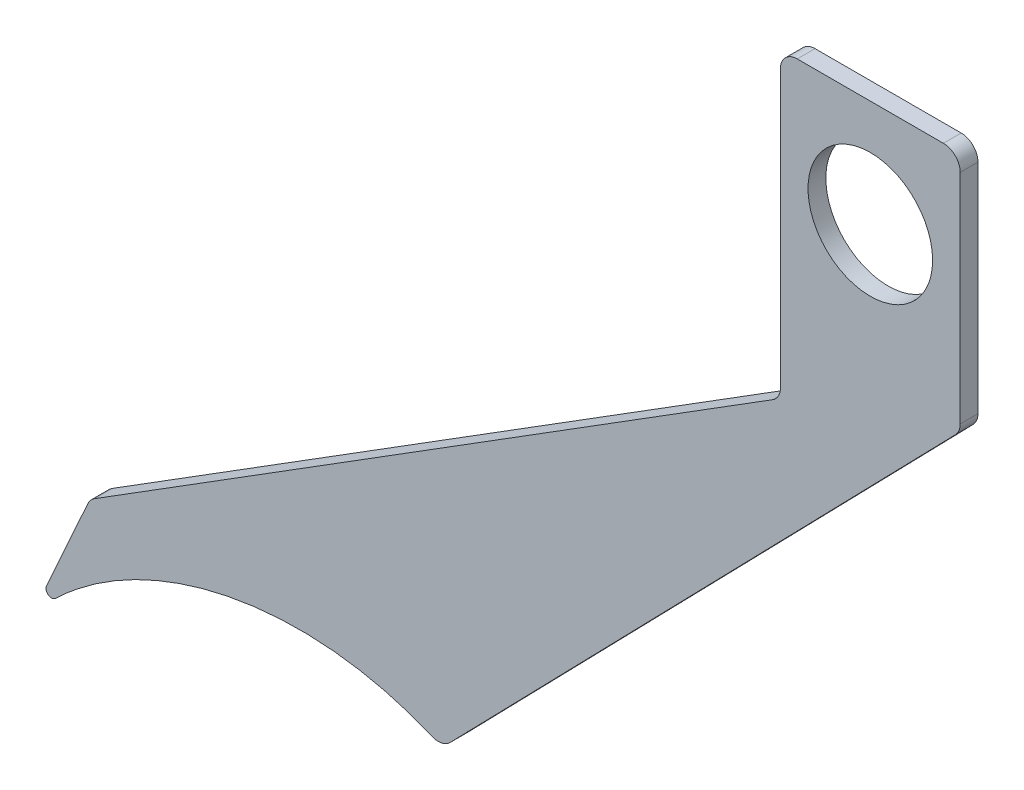
SolidWorks part; units mm, degrees
ref_plane "Front Plane" through (0, 0, 0) normal (0, 0, 1) x (1, 0, 0)
ref_plane "Top Plane" through (0, 0, 0) normal (0, 1, 0) x (1, 0, 0)
ref_plane "Right Plane" through (0, 0, 0) normal (1, 0, 0) x (0, 0, -1)
sketch "Sketch2" plane through (0, 0, 0) normal (0, 0, 1) x (1, 0, 0)
  line L0 (-364.9646, 28.575) -> (-397.0354, 28.575) construction
  line L1 (-397.0354, 28.575) -> (-397.0354, 0) construction
  line L2 (-397.0354, 0) -> (-392.1125, 0) construction
  line L3 (-369.8875, 0) -> (-364.9646, 0) construction
  line L4 (-364.9646, 0) -> (-364.9646, 28.575) construction
  line L5 (-364.9646, 0) -> (-369.8875, 0) construction
  line L6 (-392.1125, 0) -> (-397.0354, 0) construction
  line L7 (-397.0354, 0) -> (-397.0354, -28.575) construction
  line L8 (-397.0354, -28.575) -> (-364.9646, -28.575) construction
  line L9 (-364.9646, -28.575) -> (-364.9646, 0) construction
  line L10 (-364.9646, 28.575) -> (-397.0354, 28.575)
  line L11 (-397.0354, 28.575) -> (-397.0354, 0)
  line L12 (-397.0354, 0) -> (-392.1125, 0)
  line L13 (-369.8875, 0) -> (-364.9646, 0)
  line L14 (-364.9646, 0) -> (-364.9646, 28.575)
  line L15 (-364.9646, 0) -> (-369.8875, 0)
  line L16 (-392.1125, 0) -> (-397.0354, 0)
  line L17 (-397.0354, 0) -> (-397.0354, -28.575)
  line L18 (-397.0354, -28.575) -> (-364.9646, -28.575) construction
  line L19 (-364.9646, -28.575) -> (-364.9646, 0)
  line L20 (-364.9646, -28.575) -> (-454.4651, -120.5385)
  line L21 (-397.0354, -28.575) -> (-397.0354, -34.925)
  line L22 (-397.0354, -34.925) -> (-520.2077, -112.081)
  line L23 (-520.2077, -112.081) -> (-530.4646, -134.88)
  line L24 (-397.0354, 19.05) -> (-364.9646, 19.05) construction
  line L25 (-397.0354, 19.05) -> (-364.9646, 19.05)
  line L26 (-457.4205, -119.0229) -> (-364.9646, -24.0227)
  line L29 (-364.9646, 28.575) -> (-397.0354, 28.575)
  line L30 (-397.0354, 28.575) -> (-397.0354, 0)
  line L31 (-397.0354, 0) -> (-392.1125, 0)
  line L32 (-369.8875, 0) -> (-364.9646, 0)
  line L33 (-364.9646, 0) -> (-364.9646, 28.575)
  line L34 (-364.9646, 28.575) -> (-397.0354, 28.575)
  line L35 (-397.0354, 28.575) -> (-397.0354, 0)
  line L36 (-397.0354, 0) -> (-392.1125, 0)
  line L37 (-369.8875, 0) -> (-364.9646, 0)
  line L38 (-364.9646, 0) -> (-364.9646, 28.575)
  arc A0 (-369.8875, 0) -> (-392.1125, 0) centre (-381, 0) ccw construction
  arc A1 (-392.1125, 0) -> (-369.8875, 0) centre (-381, 0) ccw construction
  arc A2 (-369.8875, 0) -> (-392.1125, 0) centre (-381, 0) ccw
  arc A3 (-392.1125, 0) -> (-369.8875, 0) centre (-381, 0) ccw
  arc A5 (-369.8875, 0) -> (-392.1125, 0) centre (-381, 0) ccw
  arc A6 (-369.8875, 0) -> (-392.1125, 0) centre (-381, 0) ccw
  spline S0 degree 3 poles (-2023.9608, -1325.9834) (1605.0575, 533.461) (-2687.4182, -122.0278) (1324.895, -823.1199) knots -3.777952 -3.777952 -3.777952 -3.777952 4.743943 4.743943 4.743943 4.743943 only from (-454.4651, -120.5385) to (-530.4646, -134.88) construction
  spline S1 degree 3 poles (-454.4651, -120.5385) (-478.5685, -107.2009) (-512.5689, -113.3004) (-530.4646, -134.88) knots 0.002768 0.002768 0.002768 0.002768 1 1 1 1
  line M4 (-364.9646, 0) -> (-369.8875, 0)
  arc M5 (-369.8875, 0) -> (-392.1125, 0) centre (-381, 0) cw
  line M6 (-392.1125, 0) -> (-397.0354, 0)
  line M7 (-397.0354, 0) -> (-397.0354, -28.575)
  line M8 (-397.0354, -28.575) -> (-364.9646, -28.575)
  line M9 (-364.9646, -28.575) -> (-364.9646, 0)
  dimension "D1" = 6.35
  dimension "D2" = 25
  dimension "D3" = 20
  dimension "D5" = 3.175
  dimension "D4" = 0
extrude "Boss-Extrude1" add sketch "Sketch2" along normal blind 3.175 contours A2 L14 L25 L11 M4 M6 | M9 M4 M5 M6 M7 M8 | S1 L20 L21 L22 L23 M8
fillet "Fillet1" radius 3 6 edges at (-520.2077, -112.081, 1.5875) (-397.0354, -34.925, 1.5875) (-457.4205, -119.0229, 1.5875) (-364.9646, -24.0227, 1.5875) (-397.0354, 19.05, 1.5875) (-364.9646, 19.05, 1.5875)
fillet "Fillet2" radius 1 1 edges at (-530.4646, -134.88, 1.5875)
